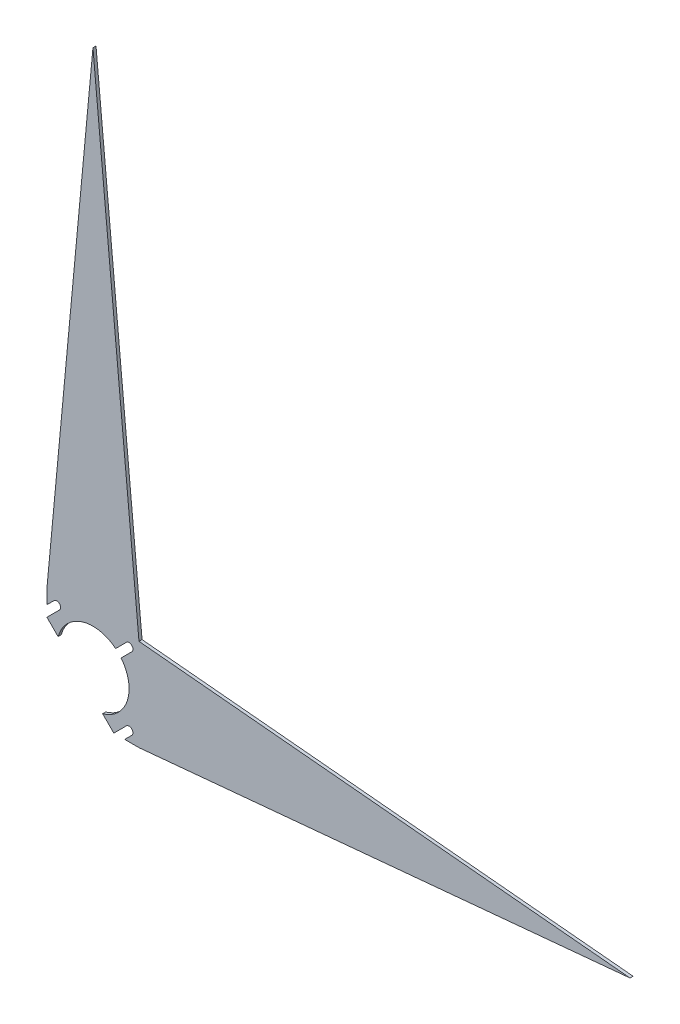
SolidWorks part; units mm, degrees
ref_plane "前视基准面" through (0, 0, 0) normal (0, 0, 1) x (1, 0, 0)
ref_plane "上视基准面" through (0, 0, 0) normal (0, 1, 0) x (1, 0, 0)
ref_plane "右视基准面" through (0, 0, 0) normal (1, 0, 0) x (0, 0, -1)
sketch "草图1" plane through (0, 0, 0) normal (0, 0, 1) x (1, 0, 0)
  line L0 (0, 0) -> (47.14, -47.14) construction
  line L1 (0, 0) -> (47.14, 0) construction
  line L2 (0, 0) -> (0, -47.14) construction
  line L3 (0, -47.14) -> (47.14, -47.14) construction
  line L4 (47.14, 0) -> (47.14, -47.14) construction
  line L5 (23.57, -23.57) -> (373.57, -23.57) construction
  line L6 (23.57, -23.57) -> (23.57, 326.43) construction
  line L7 (53.57, -53.57) -> (373.57, -23.57)
  line L8 (-6.43, -53.57) -> (53.57, -53.57)
  line L9 (-6.43, -53.57) -> (-6.43, 6.43)
  line L10 (-6.43, 6.43) -> (53.57, 6.43) construction
  line L11 (53.57, -53.57) -> (53.57, 6.43) construction
  line L12 (-6.43, -53.57) -> (53.57, 6.43) construction
  line L13 (-6.43, 6.43) -> (53.57, -53.57) construction
  line L14 (373.57, -23.57) -> (53.57, 6.43)
  line L15 (53.57, 6.43) -> (23.57, 326.43)
  line L16 (23.57, 326.43) -> (-6.43, 6.43)
  circle A0 centre (0, 0) radius 2.5
  circle A1 centre (47.14, 0) radius 2.5
  circle A2 centre (0, -47.14) radius 2.5
  circle A3 centre (47.14, -47.14) radius 2.5
  circle A4 centre (23.57, -23.57) radius 23.57
  dimension "D2" = 5
  dimension "D1" = 350
  dimension "D3" = 47.14
  dimension "D4" = 60
extrude "凸台-拉伸1" add sketch "草图1" along normal blind 2
sketch "草图2" plane through (0, 0, 2) normal (0, 0, 1) x (1, 0, 0)
  line L0 (53.57, 6.43) -> (-6.43, -53.57) construction
  line L1 (1.7678, -1.7678) -> (-27.4996, -31.0351) construction
  line L2 (-1.7678, 1.7678) -> (-23.2249, -19.6894)
  line L3 (45.3722, -45.3722) -> (19.8405, -70.9039) construction
  line L4 (48.9078, -48.9078) -> (27.5058, -70.3097)
  line L5 (-6.43, -9.9655) -> (37.1745, -53.57)
  line L6 (-6.43, 6.43) -> (-6.43, -53.57) construction
  line L7 (-6.43, -53.57) -> (53.57, -53.57) construction
  line L8 (-1.7678, 1.7678) -> (1.7678, -1.7678)
  line L9 (45.3722, -45.3722) -> (48.9078, -48.9078)
  line L10 (27.5058, -70.3097) -> (11.8066, -99.6399)
  line L11 (11.8066, -99.6399) -> (-61.4189, -41.5788)
  line L12 (-61.4189, -41.5788) -> (-48.1417, -16.7735)
  line L13 (-48.1417, -16.7735) -> (-23.2249, -19.6894)
  line L14 (-6.43, -9.9655) -> (1.7678, -1.7678)
  line L15 (37.1745, -53.57) -> (45.3722, -45.3722)
  line L16 (45.3722, 1.7678) -> (27.5058, -16.0986)
  line L17 (48.9078, -1.7678) -> (32.1009, -18.5747)
  line L18 (45.3722, 1.7678) -> (48.9078, -1.7678)
  line L19 (27.5058, -16.0986) -> (32.1009, -18.5747)
  circle A0 centre (0, 0) radius 2.5 construction
  circle A1 centre (47.14, -47.14) radius 2.5 construction
  circle A2 centre (47.14, 0) radius 2.5 construction
  dimension "D1" = 5
  dimension "D2" = 5
  dimension "D3" = 5
extrude "切除-拉伸1" cut sketch "草图2" against normal blind 2
